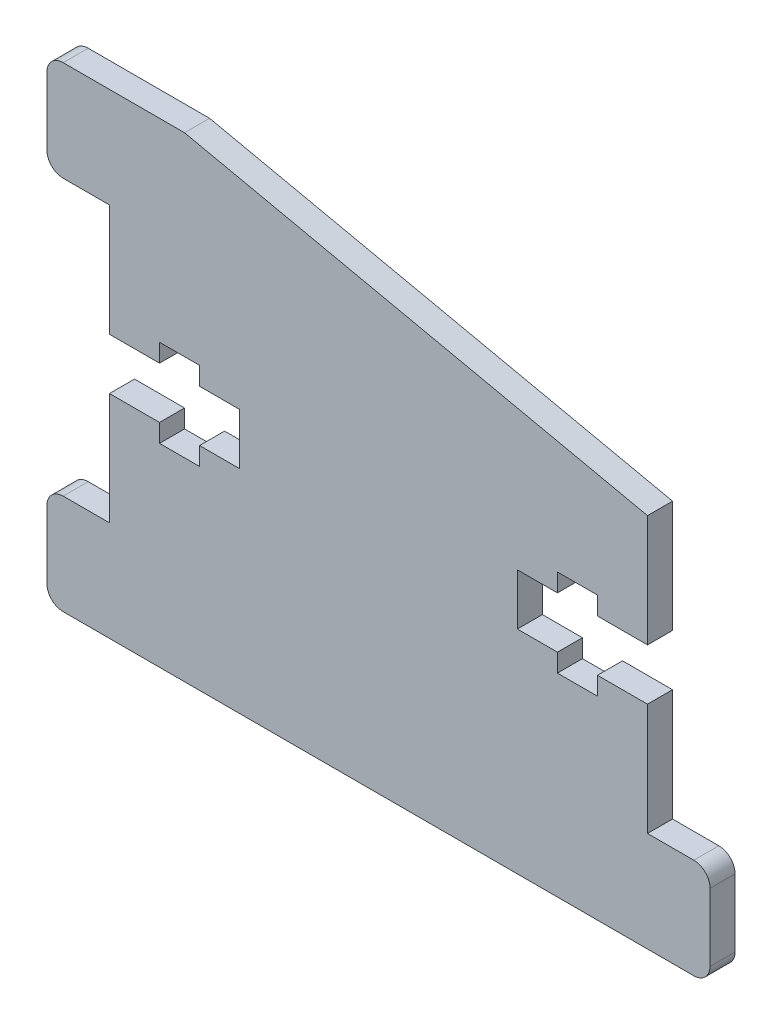
SolidWorks part; units mm, degrees
ref_plane "前视基准面" through (0, 0, 0) normal (0, 0, 1) x (1, 0, 0)
ref_plane "上视基准面" through (0, 0, 0) normal (0, 1, 0) x (1, 0, 0)
ref_plane "右视基准面" through (0, 0, 0) normal (1, 0, 0) x (0, 0, -1)
sketch "草图1" plane through (0, 0, 0) normal (0, 0, 1) x (1, 0, 0)
  line L0 (-35.5238, 30.2399) -> (-30.5238, 30.2399)
  line L1 (-35.5238, 30.2399) -> (-35.5238, 38.2399)
  line L2 (-35.5238, 38.2399) -> (-30.5238, 38.2399)
  line L3 (-30.5238, 38.2399) -> (-30.5238, 47.1899)
  line L4 (-30.5238, 47.1899) -> (-26.5238, 47.1899)
  line L5 (-26.5238, 47.1899) -> (-26.5238, 45.7399)
  line L6 (-26.5238, 45.7399) -> (-23.3238, 45.7399)
  line L7 (-23.3238, 45.7399) -> (-23.3238, 47.1899)
  line L8 (-23.3238, 47.1899) -> (-20.1238, 47.1899)
  line L9 (-20.1238, 47.1899) -> (-20.1238, 51.2899)
  line L10 (-20.1238, 51.2899) -> (-23.3238, 51.2899)
  line L11 (-23.3238, 51.2899) -> (-23.3238, 52.7399)
  line L12 (-23.3238, 52.7399) -> (-26.5238, 52.7399)
  line L13 (-26.5238, 52.7399) -> (-26.5238, 51.2899)
  line L14 (-26.5238, 51.2899) -> (-30.5238, 51.2899)
  line L15 (-30.5238, 60.2399) -> (-30.5238, 51.2899)
  line L16 (-20.1238, 49.2399) -> (-21.8238, 49.2399) construction
  line L17 (-35.5238, 60.2399) -> (-30.5238, 60.2399)
  line L18 (-35.5238, 68.2399) -> (-35.5238, 60.2399)
  line L19 (-35.5238, 68.2399) -> (-30.5238, 68.2399)
  line L20 (-30.5238, 30.2399) -> (12.4762, 30.2399)
  line L21 (-9.0238, 30.2399) -> (-9.0238, 32.8335) construction
  line L22 (12.4762, 60.2399) -> (12.4762, 51.2899)
  line L23 (2.0762, 49.2399) -> (3.7762, 49.2399) construction
  line L24 (8.4762, 51.2899) -> (12.4762, 51.2899)
  line L25 (8.4762, 52.7399) -> (8.4762, 51.2899)
  line L26 (5.2762, 52.7399) -> (8.4762, 52.7399)
  line L27 (5.2762, 51.2899) -> (5.2762, 52.7399)
  line L28 (2.0762, 51.2899) -> (5.2762, 51.2899)
  line L29 (2.0762, 47.1899) -> (2.0762, 51.2899)
  line L30 (5.2762, 47.1899) -> (2.0762, 47.1899)
  line L31 (5.2762, 45.7399) -> (5.2762, 47.1899)
  line L32 (8.4762, 45.7399) -> (5.2762, 45.7399)
  line L33 (8.4762, 47.1899) -> (8.4762, 45.7399)
  line L34 (12.4762, 47.1899) -> (8.4762, 47.1899)
  line L35 (12.4762, 38.2399) -> (12.4762, 47.1899)
  line L36 (17.4762, 38.2399) -> (12.4762, 38.2399)
  line L37 (17.4762, 30.2399) -> (17.4762, 38.2399)
  line L38 (17.4762, 30.2399) -> (12.4762, 30.2399)
  line L39 (12.4762, 60.2399) -> (-24.5238, 68.2399)
  line L40 (-24.5238, 68.2399) -> (-30.5238, 68.2399)
  point P43 (-24.9238, 45.7399)
  dimension "D1" = 3.2
  dimension "D2" = 4.1
  dimension "D3" = 7
  dimension "D4" = 11
  dimension "D5" = 5
  dimension "D6" = 8
  dimension "D7" = 43
  dimension "D8" = 4
extrude "凸台-拉伸1" add sketch "草图1" along normal blind 2
fillet "圆角1" radius 1.3 6 edges at (17.4762, 38.2399, 1) (17.4762, 30.2399, 1) (-35.5238, 68.2399, 1) (-35.5238, 60.2399, 1) (-35.5238, 38.2399, 1) (-35.5238, 30.2399, 1)
sketch "草图2" plane through (-30.5238, 0, 0) normal (-1, 0, 0) x (0, 0, 1)
  line L0 (1, 51.2899) -> (1, 47.1899)
  line L1 (2, 51.2899) -> (0, 51.2899) construction
  line L2 (2, 47.1899) -> (0, 47.1899) construction
  circle A0 centre (1, 49.2399) radius 2.05
